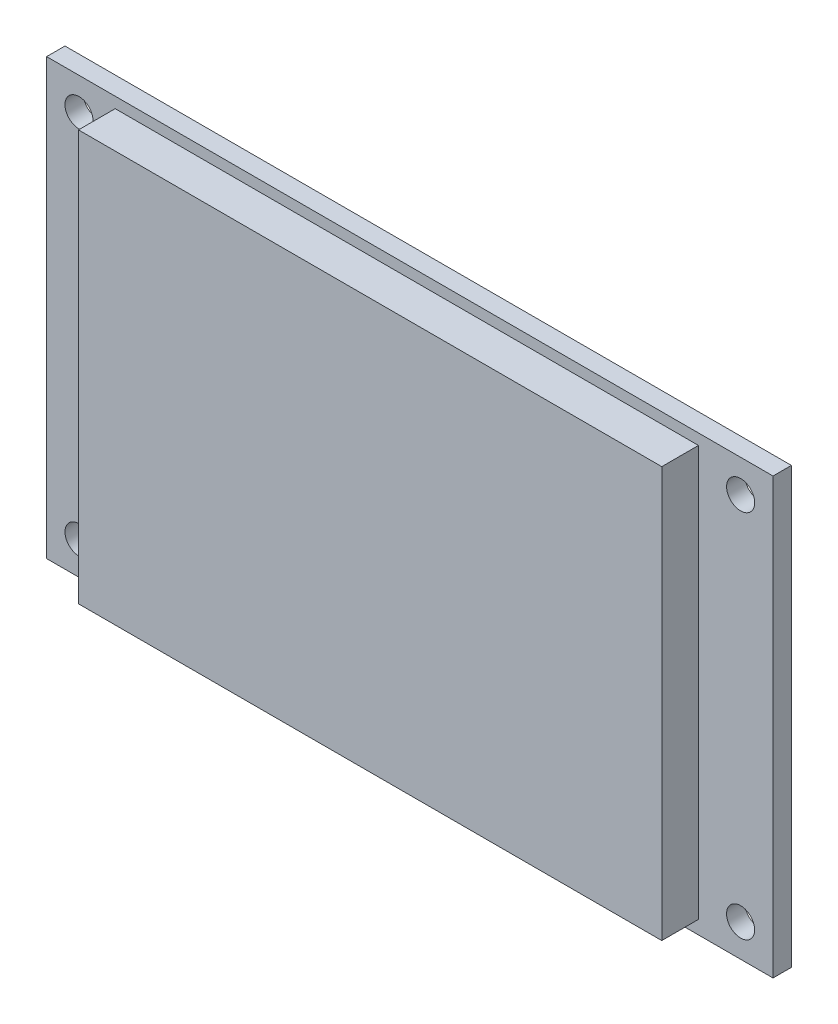
SolidWorks part; units mm, degrees
material "A-Стеклянное волокно"
ref_plane "Спереди" through (0, 0, 0) normal (0, 0, 1) x (1, 0, 0)
ref_plane "Сверху" through (0, 0, 0) normal (0, 1, 0) x (1, 0, 0)
ref_plane "Справа" through (0, 0, 0) normal (1, 0, 0) x (0, 0, -1)
sketch "Эскиз1" plane through (0, 0, 0) normal (0, 0, 1) x (1, 0, 0)
  line L1 (-33.625, -20.125) -> (33.625, -20.125)
  line L2 (-33.625, -20.125) -> (-33.625, 20.125)
  line L3 (-33.625, 20.125) -> (33.625, 20.125)
  line L4 (33.625, -20.125) -> (33.625, 20.125)
  line L5 (-33.625, -20.125) -> (33.625, 20.125) construction
  line L6 (-33.625, 20.125) -> (33.625, -20.125) construction
  point P0 (0, 0)
  dimension "D1" = 67.25
  dimension "D2" = 40.25
extrude "Бобышка-Вытянуть1" add sketch "Эскиз1" along normal blind 1.7
sketch "Эскиз2" plane through (0, 0, 1.7) normal (0, 0, 1) x (1, 0, 0)
  line L0 (-33.625, 20.125) -> (-33.625, -20.125) construction
  line L1 (-27.275, -18.875) -> (26.725, -18.875)
  line L2 (-27.275, -18.875) -> (-27.275, 19.125)
  line L3 (-27.275, 19.125) -> (26.725, 19.125)
  line L4 (26.725, -18.875) -> (26.725, 19.125)
  line L5 (-27.275, -18.875) -> (26.725, 19.125) construction
  line L6 (-27.275, 19.125) -> (26.725, -18.875) construction
  line L7 (33.625, -20.125) -> (33.625, 20.125) construction
  line L8 (33.625, 20.125) -> (-33.625, 20.125) construction
  point P0 (-0.275, 0.125)
  point P5 (2.2948, 0)
  dimension "D1" = 38
  dimension "D2" = 54
  dimension "D3" = 6.35
  dimension "D4" = 6.9
  dimension "D5" = 1
extrude "Бобышка-Вытянуть2" add sketch "Эскиз2" along normal blind 3.4
sketch "Эскиз3" plane through (0, 0, 1.7) normal (0, 0, 1) x (1, 0, 0)
  line L0 (33.625, 20.125) -> (-33.625, 20.125) construction
  line L1 (-30.625, -17.125) -> (30.625, -17.125) construction
  line L2 (-30.625, -17.125) -> (-30.625, 17.125) construction
  line L3 (-30.625, 17.125) -> (30.625, 17.125) construction
  line L4 (30.625, -17.125) -> (30.625, 17.125) construction
  line L5 (-30.625, -17.125) -> (30.625, 17.125) construction
  line L6 (-30.625, 17.125) -> (30.625, -17.125) construction
  line L7 (-33.625, 20.125) -> (-33.625, -20.125) construction
  point P0 (0, 0)
  dimension "D1" = 3
  dimension "D2" = 3
hole_wizard "Отверстие с зазором M21" positions "Эскиз4" profile "Эскиз5" hole size "M2" standard "ISO" end condition through all
sketch "Эскиз4" plane through (0, 0, 1.7) normal (0, 0, 1) x (1, 0, 0)
  point P0 (-30.625, 17.125)
  point P3 (-30.625, -17.125)
  point P6 (30.625, -17.125)
  point P9 (30.625, 17.125)
sketch "Эскиз5" plane through (-30.625, 17.125, 1.7) normal (1, 0, 0) x (0, -1, 0)
  line L0 (0, 0) -> (0, 1.7)
  line L1 (0, 1.7) -> (1.3, 1.7)
  line L2 (1.3, 1.7) -> (1.3, 0)
  line L5 (1.3, 0) -> (0, 0)
  line L11 (0, -6.35) -> (0, 107.95) construction
  dimension "Диаметр сквозного отверстия" = 2.6
  dimension "Глубина сквозного отверстия" = 1.7
